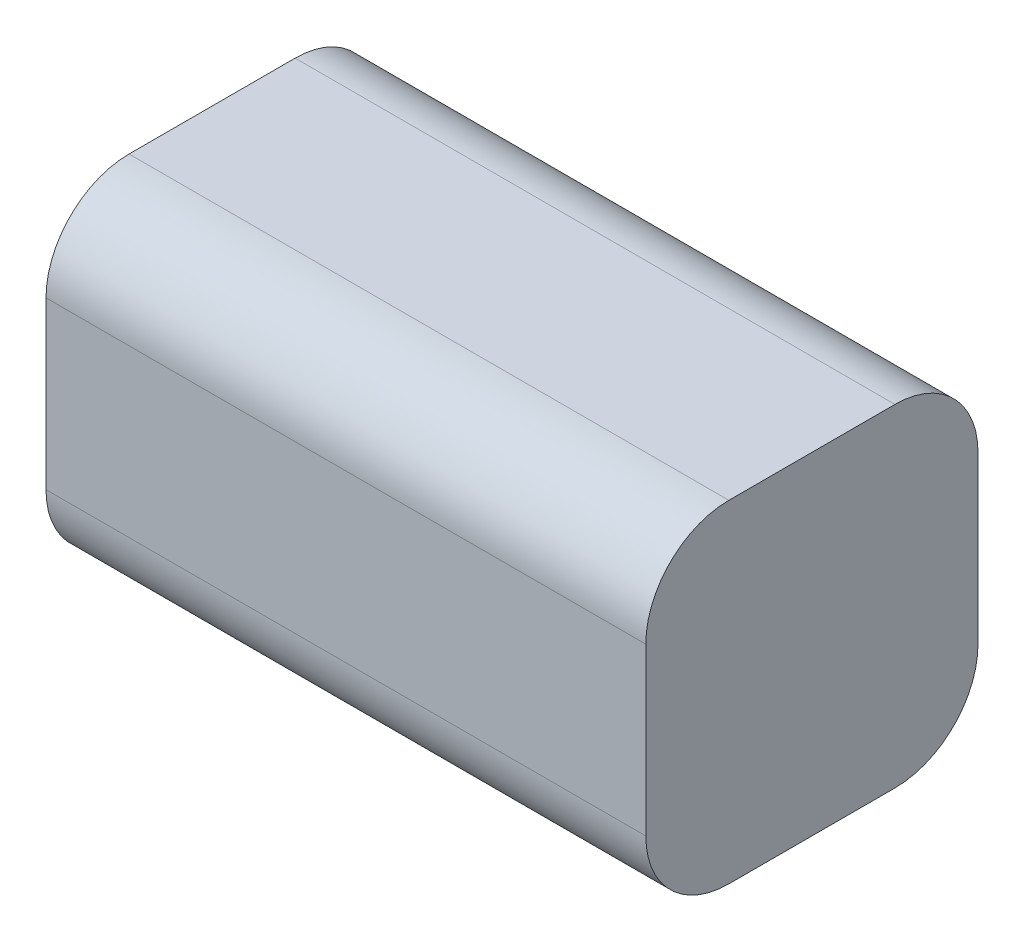
SolidWorks part; units mm, degrees
ref_plane "Front Plane" through (0, 0, 0) normal (0, 0, 1) x (1, 0, 0)
ref_plane "Top Plane" through (0, 0, 0) normal (0, 1, 0) x (1, 0, 0)
ref_plane "Right Plane" through (0, 0, 0) normal (1, 0, 0) x (0, 0, -1)
sketch "Sketch1" plane through (0, 0, 0) normal (0, 1, 0) x (1, 0, 0)
  line L1 (-32.5, -18) -> (32.5, -18)
  line L2 (-32.5, -18) -> (-32.5, 18)
  line L3 (-32.5, 18) -> (32.5, 18)
  line L4 (32.5, -18) -> (32.5, 18)
  line L5 (-32.5, -18) -> (32.5, 18) construction
  line L6 (-32.5, 18) -> (32.5, -18) construction
  point P0 (0, 0)
  dimension "D1" = 65
  dimension "D2" = 36
extrude "Boss-Extrude1" add sketch "Sketch1" along normal mid plane 36
fillet "Fillet1" radius 9 4 edges at (0, -18, -18) (0, 18, -18) (0, -18, 18) (0, 18, 18)
